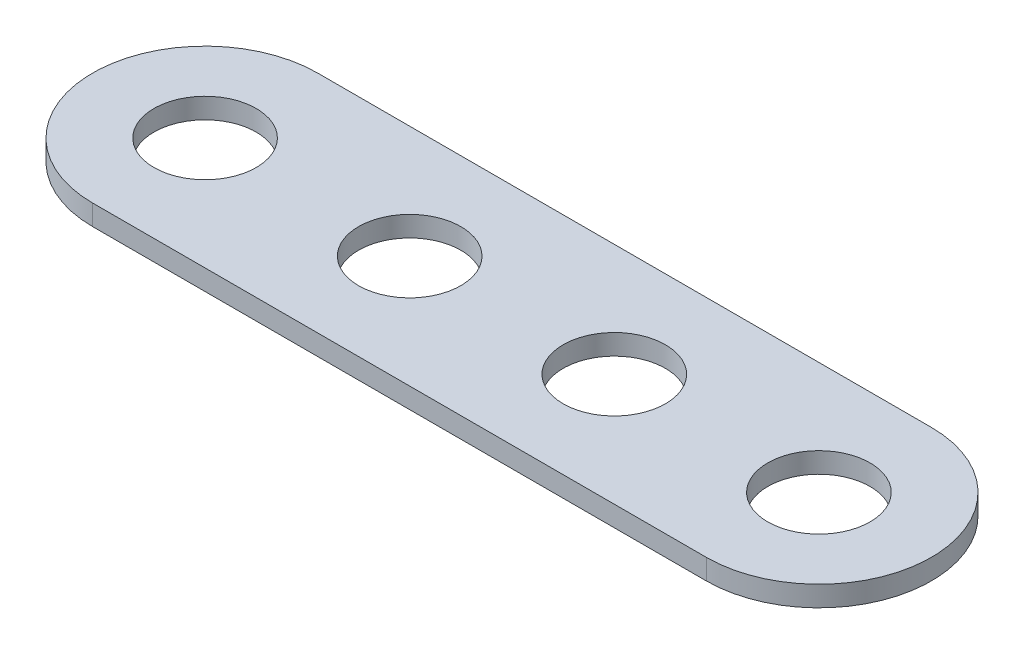
SolidWorks part; units mm, degrees
material "1.4000 (X6Cr13)"
ref_plane "Ebene vorne" through (0, 0, 0) normal (0, 0, 1) x (1, 0, 0)
ref_plane "Ebene oben" through (0, 0, 0) normal (0, 1, 0) x (1, 0, 0)
ref_plane "Ebene rechts" through (0, 0, 0) normal (1, 0, 0) x (0, 0, -1)
sketch "Skizze1" plane through (0, 0, 0) normal (0, 1, 0) x (1, 0, 0)
  line L0 (0, 0) -> (-30, 0) construction
  line L1 (0, -5.5) -> (-30, -5.5)
  line L2 (0, 5.5) -> (-30, 5.5)
  arc A0 (0, -5.5) -> (0, 5.5) centre (0, 0) ccw
  arc A1 (-30, 5.5) -> (-30, -5.5) centre (-30, 0) ccw
  circle A2 centre (0, 0) radius 2.5
  circle A3 centre (-20, 0) radius 2.5
  circle A4 centre (-10, 0) radius 2.5
  circle A5 centre (-30, 0) radius 2.5
  point P3 (-15, 0)
  dimension "D3" = 5
  dimension "D1" = 11
  dimension "D2" = 30
  dimension "D4" = 10
  dimension "D5" = 10
extrude "Aufsatz-Linear austragen1" add sketch "Skizze1" along normal blind 1
